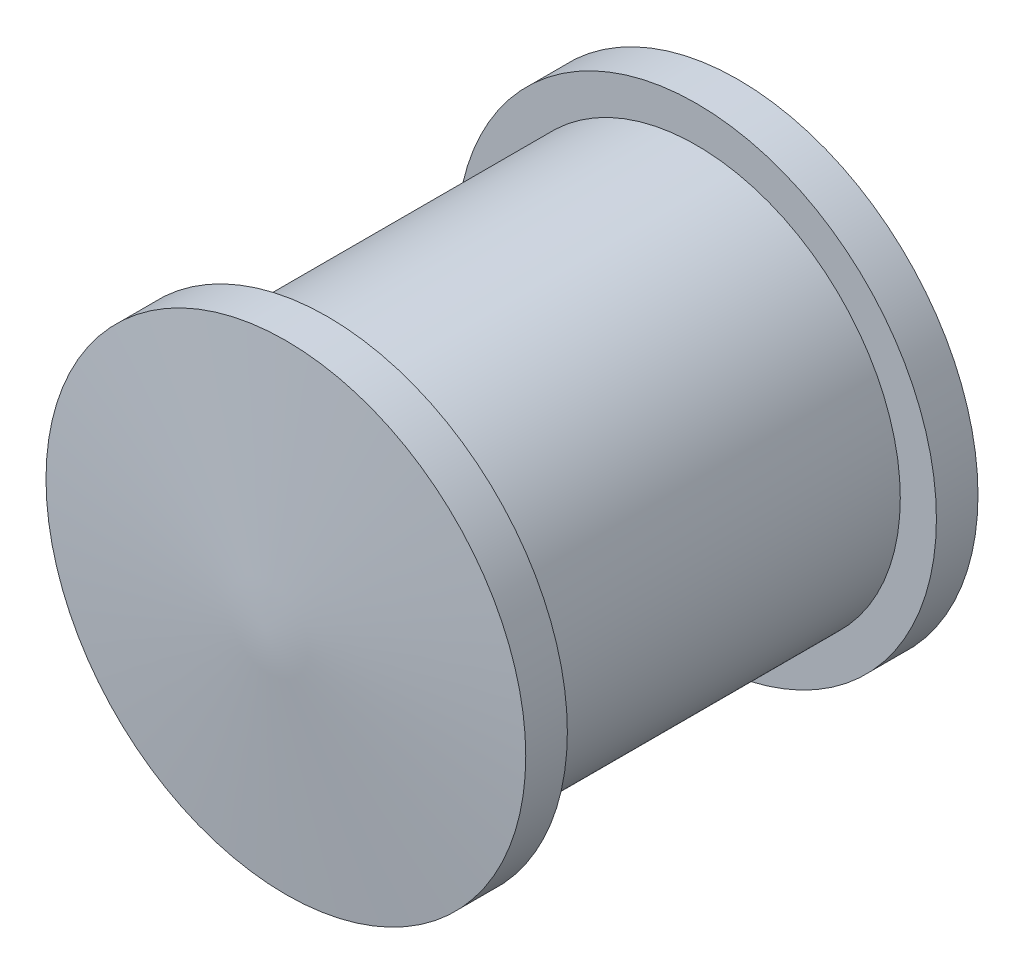
SolidWorks part; units mm, degrees
ref_plane "Front Plane" through (0, 0, 0) normal (0, 0, 1) x (1, 0, 0)
ref_plane "Top Plane" through (0, 0, 0) normal (0, 1, 0) x (1, 0, 0)
ref_plane "Right Plane" through (0, 0, 0) normal (1, 0, 0) x (0, 0, -1)
sketch "Sketch2" plane through (0, 0, 0) normal (0, 1, 0) x (1, 0, 0)
  line L0 (0, 0) -> (0, 30.8)
  line L1 (0, 0) -> (14.95, 1.308)
  line L2 (14.95, 1.308) -> (14.95, 3.9)
  line L3 (14.95, 3.9) -> (12.7, 3.9)
  line L4 (12.7, 3.9) -> (12.7, 26.9)
  line L5 (12.7, 26.9) -> (14.95, 26.9)
  line L6 (14.95, 26.9) -> (14.95, 29.492)
  line L7 (14.95, 29.492) -> (0, 30.8)
  line L8 (0, 15.4) -> (24.1462, 15.4) construction
  point P3 (14.95, 2.1899)
  dimension "D1" = 12.7
  dimension "D2" = 14.95
  dimension "D3" = 14.95
  dimension "D4" = 23
  dimension "D5" = 3.9
  dimension "D6" = 3.9
  dimension "D7" = 5
  dimension "D8" = 5
  dimension "D9" = 30.8
revolve "Revolve1" add sketch "Sketch2" angle 360 about L0
